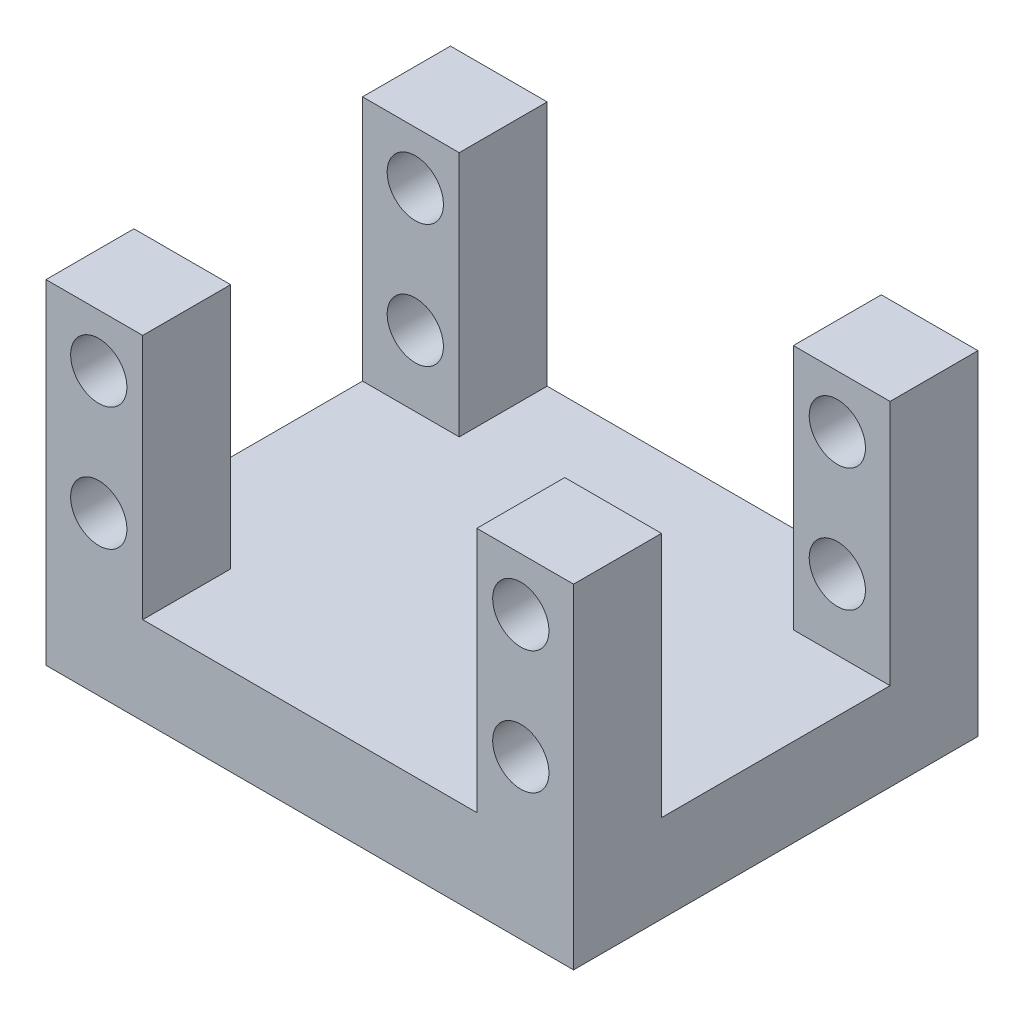
SolidWorks part; units mm, degrees
ref_plane "前视基准面" through (0, 0, 0) normal (0, 0, 1) x (1, 0, 0)
ref_plane "上视基准面" through (0, 0, 0) normal (0, 1, 0) x (1, 0, 0)
ref_plane "右视基准面" through (0, 0, 0) normal (1, 0, 0) x (0, 0, -1)
other "Configuration Table"
sketch "草图1" plane through (0, 0, 0) normal (0, 0, 1) x (1, 0, 0)
  line L0 (0, 9) -> (0, -9.5) construction
  line L1 (-15, -9.5) -> (15, -9.5)
  line L2 (-15, -9.5) -> (-15, 9.5)
  line L3 (-15, 9.5) -> (-9.5, 9.5)
  line L4 (15, -9.5) -> (15, 9.5)
  line L5 (-15, -9.5) -> (15, 9.5) construction
  line L6 (-15, 9.5) -> (15, -9.5) construction
  line L7 (9.5, 9.5) -> (15, 9.5)
  line L8 (-9.5, -4.5) -> (9.5, -4.5)
  line L9 (-9.5, -4.5) -> (-9.5, 9.5)
  line L11 (9.5, -4.5) -> (9.5, 9.5)
  line L12 (-9.5, -4.5) -> (9.5, 9.5) construction
  line L13 (-9.5, 9.5) -> (9.5, -4.5) construction
  point P0 (0, 0)
  point P8 (0, 2.5)
  dimension "D1" = 30
  dimension "D2" = 14
  dimension "D3" = 19
  dimension "D4" = 5
extrude "凸台-拉伸1" add sketch "草图1" along normal blind 23
hole_wizard "孔1" positions "草图2" profile "草图3" legacy end condition through all
sketch "草图2" plane through (0, 0, 0) normal (0, 0, -1) x (-1, 0, 0)
  point P0 (12, 6.5)
  point P3 (12, -0.5)
  point P6 (-12, -0.5)
  point P9 (-12, 6.5)
sketch "草图3" plane through (-12, 6.5, 0) normal (1, 0, 0) x (0, 1, 0)
  line L0 (0, 0) -> (0, 23)
  line L1 (0, 23) -> (1.6, 23)
  line L2 (1.6, 23) -> (1.6, 0)
  line L3 (1.6, 0) -> (0, 0)
  line L4 (0, 110) -> (0, -10) construction
  dimension "直径" = 3.2
  dimension "深度" = 23
sketch "草图4" plane through (15, 0, 0) normal (1, 0, 0) x (0, 0, -1)
  line L0 (-11.5, 9.5) -> (-11.5, -9.5) construction
  line L1 (-23, 9.5) -> (0, 9.5) construction
  line L2 (-23, -9.5) -> (0, -9.5) construction
  line L4 (-18, -4.5) -> (-5, -4.5)
  line L5 (-18, -4.5) -> (-18, 9.5)
  line L6 (-18, 9.5) -> (-5, 9.5)
  line L7 (-5, -4.5) -> (-5, 9.5)
  line L8 (-18, -4.5) -> (-5, 9.5) construction
  line L9 (-18, 9.5) -> (-5, -4.5) construction
  point P6 (-11.5, 2.5)
  dimension "D1" = 13
  dimension "D2" = 14
extrude "切除-拉伸1" cut sketch "草图4" against normal through all
